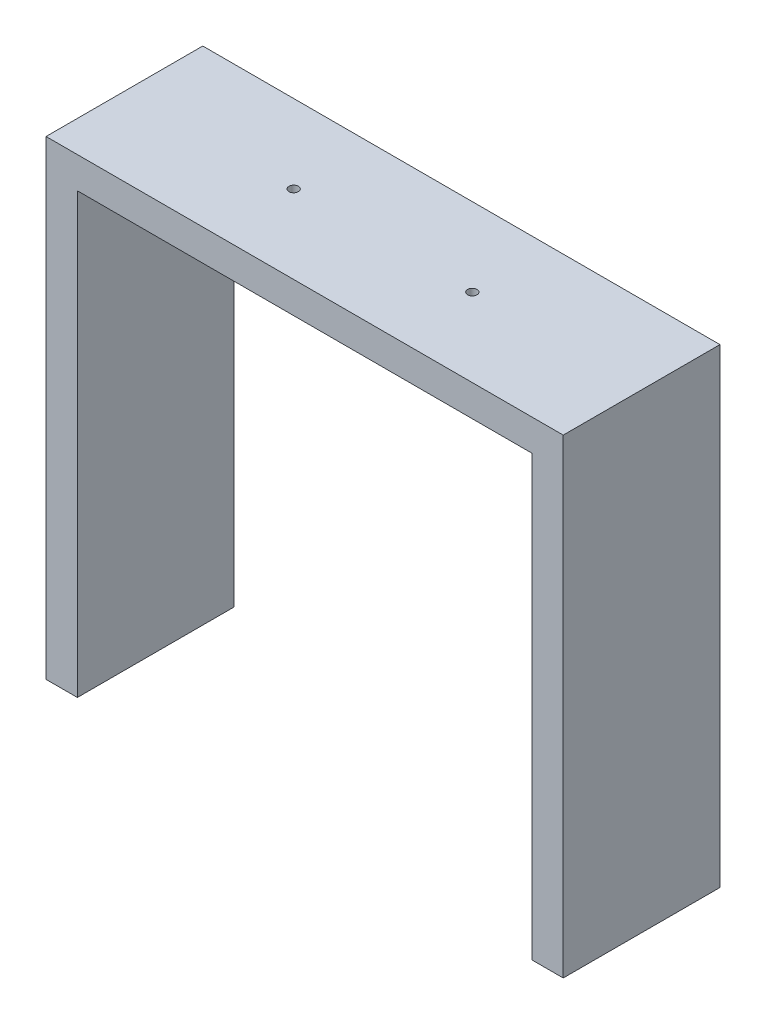
SolidWorks part; units mm, degrees
ref_plane "Front Plane" through (0, 0, 0) normal (0, 0, 1) x (1, 0, 0)
ref_plane "Top Plane" through (0, 0, 0) normal (0, 1, 0) x (1, 0, 0)
ref_plane "Right Plane" through (0, 0, 0) normal (1, 0, 0) x (0, 0, -1)
sketch "Sketch1" plane through (0, 0, 0) normal (0, 0, 1) x (1, 0, 0)
  line L0 (-155, 0) -> (155, 0) construction
  line L1 (-165, 0) -> (-145, 0)
  line L2 (0, -55) -> (0, 55) construction
  line L3 (165, 0) -> (145, 0)
  line L4 (-165, 0) -> (-165, 300)
  line L5 (-165, 300) -> (165, 300)
  line L6 (165, 300) -> (165, 0)
  line L7 (-145, 0) -> (-145, 280)
  line L8 (-145, 280) -> (145, 280)
  line L9 (145, 280) -> (145, 0)
  point P4 (0, 0)
  point P8 (-155, 0)
  dimension "D1" = 310
  dimension "D2" = 20
  dimension "D3" = 20
  dimension "D4" = 300
extrude "Boss-Extrude1" add sketch "Sketch1" along normal mid plane 100
sketch "Sketch2" plane through (0, 0, 0) normal (0, -1, 0) x (1, 0, 0)
  line L0 (-165, 0) -> (165, 0) construction
  line L1 (-165, 50) -> (-165, -50) construction
  line L2 (165, 50) -> (165, -50) construction
  line L3 (0, -55) -> (0, 55) construction
  circle A0 centre (-155, 0) radius 4
  circle A1 centre (155, 0) radius 4
  point P6 (-155, 0)
  dimension "D2" = 8
  dimension "D1" = 10
extrude "Cut-Extrude1" cut sketch "Sketch2" against normal blind 50
sketch "Sketch3" plane through (0, 300, 0) normal (0, 1, 0) x (1, 0, 0)
  line L0 (-57, 0) -> (57, 0) construction
  line L1 (0, -55) -> (0, 55) construction
  circle A0 centre (-57, 0) radius 3
  circle A1 centre (57, 0) radius 3
  point P4 (0, 0)
  dimension "D2" = 6
  dimension "D1" = 114
extrude "Cut-Extrude2" cut sketch "Sketch3" against normal through all both and the other way through all
